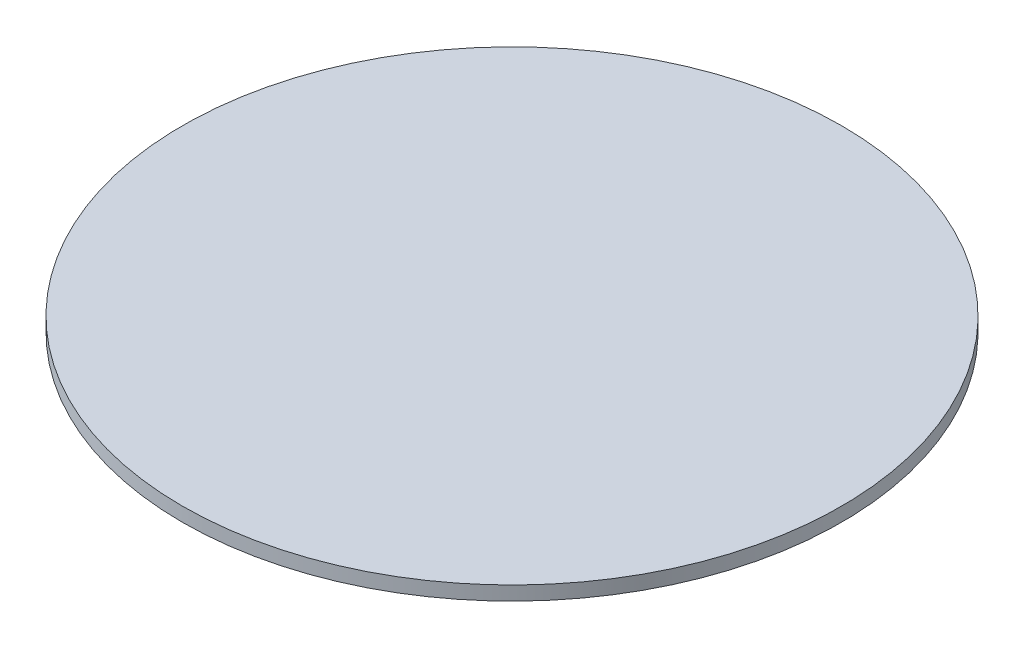
SolidWorks part; units mm, degrees
ref_plane "Front Plane" through (0, 0, 0) normal (0, 0, 1) x (1, 0, 0)
ref_plane "Top Plane" through (0, 0, 0) normal (0, 1, 0) x (1, 0, 0)
ref_plane "Right Plane" through (0, 0, 0) normal (1, 0, 0) x (0, 0, -1)
sketch "Sketch1" plane through (0, 0, 0) normal (0, 1, 0) x (1, 0, 0)
  circle A0 centre (0, 0) radius 4
  dimension "D1" = 8
extrude "Boss-Extrude1" add sketch "Sketch1" along normal blind 0.17
